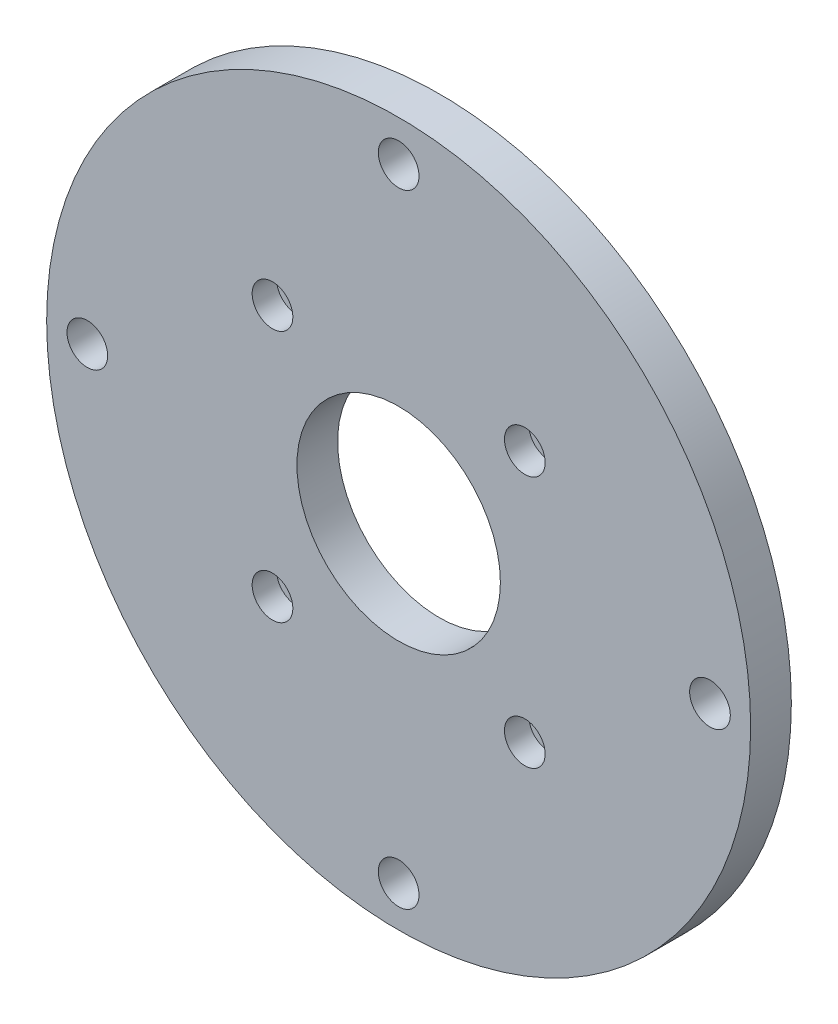
SolidWorks part; units mm, degrees
ref_plane "Front Plane" through (0, 0, 0) normal (0, 0, 1) x (1, 0, 0)
ref_plane "Top Plane" through (0, 0, 0) normal (0, 1, 0) x (1, 0, 0)
ref_plane "Right Plane" through (0, 0, 0) normal (1, 0, 0) x (0, 0, -1)
sketch "Sketch1" plane through (0, 0, 0) normal (0, 0, 1) x (1, 0, 0)
  line L1 (-15.5, -15.5) -> (15.5, -15.5) construction
  line L2 (-15.5, -15.5) -> (-15.5, 15.5) construction
  line L3 (-15.5, 15.5) -> (15.5, 15.5) construction
  line L4 (15.5, -15.5) -> (15.5, 15.5) construction
  line L5 (-15.5, -15.5) -> (15.5, 15.5) construction
  line L6 (-15.5, 15.5) -> (15.5, -15.5) construction
  circle A0 centre (0, 0) radius 43.25
  circle A2 centre (0, 0) radius 38.25 construction
  circle A3 centre (0, 38.25) radius 2.5
  circle A4 centre (38.25, 0) radius 2.5
  circle A5 centre (0, -38.25) radius 2.5
  circle A6 centre (-38.25, 0) radius 2.5
  circle A7 centre (-15.5, 15.5) radius 1.75
  circle A8 centre (15.5, 15.5) radius 1.75
  circle A9 centre (15.5, -15.5) radius 1.75
  circle A10 centre (-15.5, -15.5) radius 1.75
  circle A11 centre (0, 0) radius 12.5
  dimension "D1" = 86.5
  dimension "D2" = 5
  dimension "D3" = 5
  dimension "D4" = 5
  dimension "D5" = 5
  dimension "D6" = 5
  dimension "D9" = 3.5
  dimension "D10" = 3.5
  dimension "D11" = 3.5
  dimension "D12" = 3.5
  dimension "D13" = 25
  dimension "D7" = 31
  dimension "D8" = 31
extrude "Boss-Extrude1" add sketch "Sketch1" along normal blind 5
sketch "Sketch2" plane through (0, 0, 5) normal (0, 0, 1) x (1, 0, 0)
  circle A0 centre (-15.5, 15.5) radius 2.5
  circle A1 centre (15.5, 15.5) radius 2.5
  circle A2 centre (15.5, -15.5) radius 2.5
  circle A3 centre (-15.5, -15.5) radius 2.5
  dimension "D1" = 5
  dimension "D2" = 5
  dimension "D3" = 5
  dimension "D4" = 5
extrude "Cut-Extrude1" cut sketch "Sketch2" against normal blind 3
